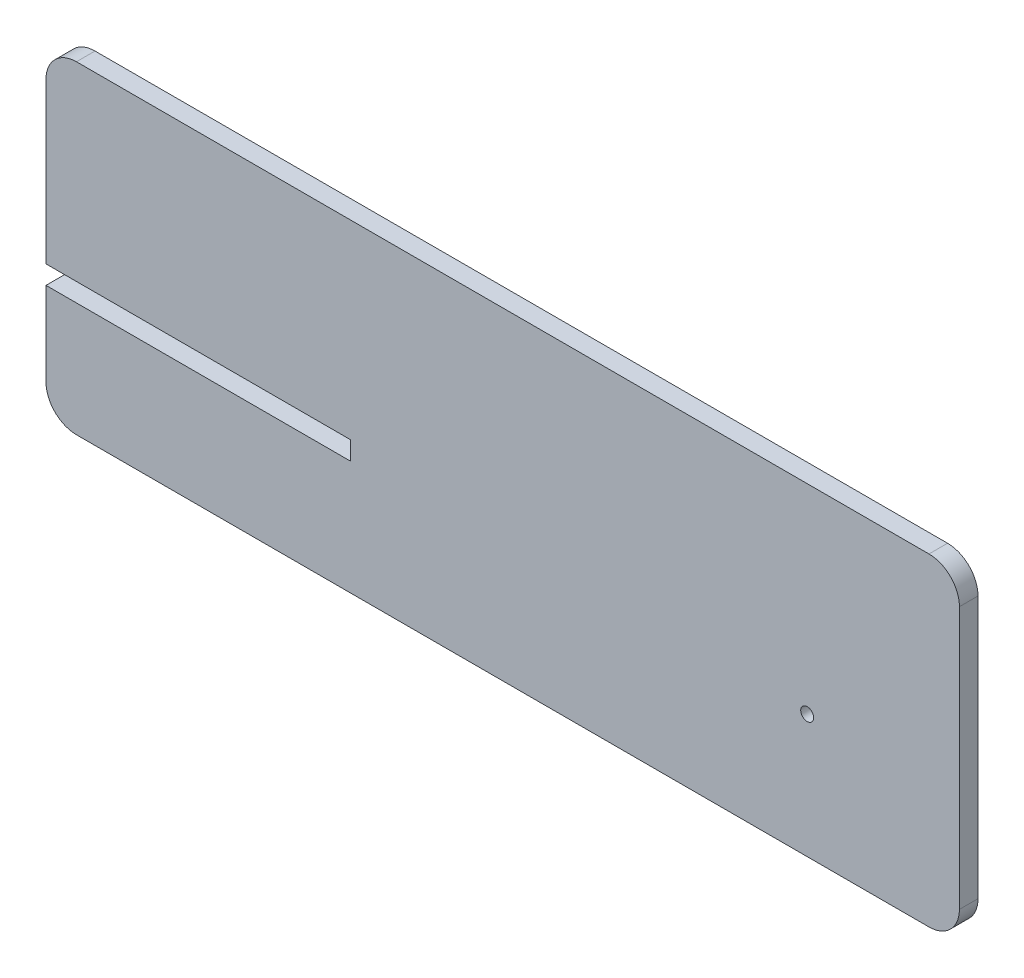
SolidWorks part; units mm, degrees
material "Corrugated Paper"
ref_plane "Front Plane" through (0, 0, 0) normal (0, 0, 1) x (1, 0, 0)
ref_plane "Top Plane" through (0, 0, 0) normal (0, 1, 0) x (1, 0, 0)
ref_plane "Right Plane" through (0, 0, 0) normal (1, 0, 0) x (0, 0, -1)
sketch "Sketch2" plane through (0, 0, 0) normal (0, 0, 1) x (1, 0, 0)
  line L0 (-50.8, 1.5494) -> (-50.8, 7.8994)
  line L1 (-50.8, -7.8994) -> (50.8, -7.8994)
  line L2 (-50.8, -7.8994) -> (-50.8, -1.5494)
  line L3 (-50.8, 7.8994) -> (50.8, 7.8994)
  line L4 (50.8, -7.8994) -> (50.8, 7.8994)
  line L5 (-50.8, -7.8994) -> (50.8, 7.8994) construction
  line L6 (-50.8, 7.8994) -> (50.8, -7.8994) construction
  line L7 (-50.8, 1.5494) -> (0, 1.5494)
  line L9 (-50.8, -1.5494) -> (0, -1.5494)
  line L10 (0, 1.5494) -> (0, -1.5494)
  point P0 (0, 0)
  dimension "D1" = 50.8
  dimension "D3" = 3.0988
  dimension "D2" = 6.35
extrude "Boss-Extrude1" add sketch "Sketch2" along normal blind 3.0988
sketch "Sketch3" plane through (0, 0, 0) normal (0, 0, 1) x (1, 0, 0)
  line L0 (-50.8, -7.8994) -> (-50.8, -20.5994)
  line L1 (-50.8, -20.5994) -> (101.6, -20.5994)
  line L2 (101.6, -20.5994) -> (101.6, 33.2994)
  line L3 (50.8, 7.8994) -> (-50.8, 7.8994) construction
  line L5 (-50.8, 33.2994) -> (-50.8, 7.8994)
  line L6 (-50.8, -7.8994) -> (50.8, -7.8994) construction
  line L7 (50.8, -7.8994) -> (50.8, 7.8994) construction
  line L8 (-50.8, -7.8994) -> (50.8, -7.8994)
  line L9 (50.8, -7.8994) -> (50.8, 7.8994)
  line L10 (50.8, 7.8994) -> (-50.8, 7.8994)
  line L13 (101.6, 33.2994) -> (-50.8, 33.2994)
  circle A0 centre (76.2, 0) radius 1.0795
  dimension "D1" = 2.159
  dimension "D2" = 12.7
  dimension "D3" = 25.4
  dimension "D4" = 152.4
  dimension "D5" = 25.4
extrude "Boss-Extrude2" add sketch "Sketch3" along normal blind 3.0988
fillet "Fillet1" radius 5.08 4 edges at (101.6, -20.5994, 1.5494) (-50.8, -20.5994, 1.5494) (-50.8, 33.2994, 1.5494) (101.6, 33.2994, 1.5494)
equation "\"rodThick\"= 0.085in"
equation "\"thick\"= 0.122in"
equation "\"clear\"= 0.003in"
equation "\"D3@Sketch2\"=\"thick\""
equation "\"D1@Boss-Extrude1\"=\"thick\""
equation "\"D1@Sketch3\"=\"rodThick\""
equation "\"D1@Boss-Extrude2\"=\"thick\""
